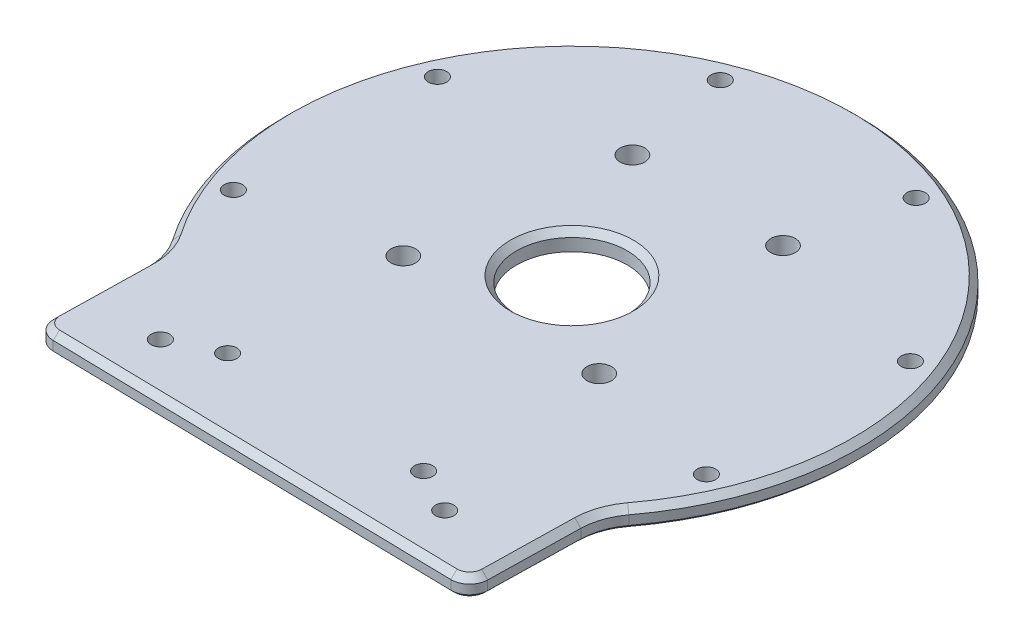
SolidWorks part; units mm, degrees
material "Hexcel AS4C (3000 丝)"
ref_plane "前视基准面" through (0, 0, 0) normal (0, 0, 1) x (1, 0, 0)
ref_plane "上视基准面" through (0, 0, 0) normal (0, 1, 0) x (1, 0, 0)
ref_plane "右视基准面" through (0, 0, 0) normal (1, 0, 0) x (0, 0, -1)
sketch "草图1" plane through (0, 78.0252, 0) normal (0, -1, 0) x (1, 0, 0)
  line L0 (-212.5412, -109.2495) -> (-212.2402, -124.0969)
  line L1 (-212.0952, -131.245) -> (-212.4804, -112.2489) construction
  line L2 (-209.6027, -106.1893) -> (-143.6162, -104.8513)
  line L3 (-140.556, -107.7898) -> (-140.255, -122.6373)
  line L4 (-140.4952, -110.7892) -> (-140.11, -129.7853) construction
  circle A0 centre (-175.5755, -156.5098) radius 46.7 construction
  circle A1 centre (-136.6484, -139.4531) radius 1.5
  circle A2 centre (-136.6484, -139.4531) radius 1.5
  circle A3 centre (-175.5755, -156.5098) radius 9
  circle A5 centre (-135.989, -171.9745) radius 1.5
  circle A6 centre (-135.989, -171.9745) radius 1.5
  circle A7 centre (-191.0402, -196.0963) radius 1.5
  circle A8 centre (-191.0402, -196.0963) radius 1.5
  circle A9 centre (-215.1621, -141.0451) radius 1.5
  circle A10 centre (-215.1621, -141.0451) radius 1.5
  circle A11 centre (-192.6323, -117.5827) radius 1.5
  circle A12 centre (-192.6323, -117.5827) radius 1.5
  circle A13 centre (-160.1109, -116.9233) radius 1.5
  circle A14 centre (-160.1109, -116.9233) radius 1.5
  circle A15 centre (-214.5026, -173.5665) radius 1.5
  circle A16 centre (-214.5026, -173.5665) radius 1.5
  circle A17 centre (-158.5188, -195.4369) radius 1.5
  circle A18 centre (-158.5188, -195.4369) radius 1.5
  circle A19 centre (-175.5755, -156.5098) radius 46.7
  circle A20 centre (-175.5755, -156.5098) radius 46.7 construction
  arc A21 (-214.0084, -129.9805) -> (-138.2497, -128.4443) centre (-175.5755, -156.5098) ccw
  arc A22 (-143.6162, -104.8513) -> (-140.556, -107.7898) centre (-143.5554, -107.8506) cw
  arc A23 (-212.5412, -109.2495) -> (-209.6027, -106.1893) centre (-209.5419, -109.1887) cw
  arc A24 (-140.255, -122.6373) -> (-138.2497, -128.4443) centre (-130.257, -122.4345) ccw
  arc A25 (-212.2402, -124.0969) -> (-214.0084, -129.9805) centre (-222.2381, -124.2997) cw
  point P12 (-140.6169, -104.7904)
  point P48 (-212.6021, -106.2501)
  point P51 (-140.186, -126.039)
  point P54 (-212.1712, -127.4986)
  dimension "D11" = 3
  dimension "D12" = 10
  dimension "D1" = 0
  dimension "D3" = 0
  dimension "D4" = 0
  dimension "D5" = 0
  dimension "D6" = 0
  dimension "D7" = 0
  dimension "D8" = 0
  dimension "D9" = 0
  dimension "D10" = 0
extrude "凸台-拉伸1" add sketch "草图1" along normal blind 3
chamfer "倒角1" distance 0.5 angle 45 8 edges at (-174.6288, 75.0252, -203.2002) (-139.7093, 75.0252, -125.6986) (-212.6613, 75.0252, -127.1778) (-140.4055, 75.0252, -115.2135) (-212.3907, 75.0252, -116.6732) (-141.4775, 75.0252, -105.6867) (-211.7058, 75.0252, -107.1108) (-176.6095, 75.0252, -105.5203)
sketch "草图3" plane through (0, 75.0252, 0) normal (0, -1, 0) x (1, 0, 0)
  circle A0 centre (-200.0412, -114.0527) radius 1.5 construction
  circle A1 centre (-200.0412, -114.0527) radius 1.5
extrude "切除-拉伸1" cut sketch "草图3" against normal through all both and the other way through all
sketch "草图4" plane through (0, 78.0252, 0) normal (0, 1, 0) x (1, 0, 0)
  circle A0 centre (-192.0646, 145.5769) radius 2 construction
  circle A1 centre (-159.5432, 144.9175) radius 2 construction
  circle A2 centre (-187.634, 178.4094) radius 2 construction
  circle A3 centre (-162.6392, 177.9026) radius 2 construction
  circle A4 centre (-192.0646, 145.5769) radius 2
  circle A5 centre (-159.5432, 144.9175) radius 2
  circle A6 centre (-187.634, 178.4094) radius 2
  circle A7 centre (-162.6392, 177.9026) radius 2
extrude "切除-拉伸2" cut sketch "草图4" against normal through all both and the other way through all
chamfer "倒角2" distance 1 angle 45 9 edges at (-166.5755, 78.0252, -156.5098) (-176.6095, 78.0252, -105.5203) (-211.7058, 78.0252, -107.1108) (-141.4775, 78.0252, -105.6867) (-212.3907, 78.0252, -116.6732) (-140.4055, 78.0252, -115.2135) (-212.6613, 78.0252, -127.1778) (-139.7093, 78.0252, -125.6986) (-174.6288, 78.0252, -203.2002)
sketch "草图5" plane through (0, 75.0252, 0) normal (0, -1, 0) x (1, 0, 0)
  circle A0 centre (-152.8511, -113.0958) radius 1.5 construction
  circle A1 centre (-152.8511, -113.0958) radius 1.5
extrude "切除-拉伸3" cut sketch "草图5" against normal through all both and the other way through all
